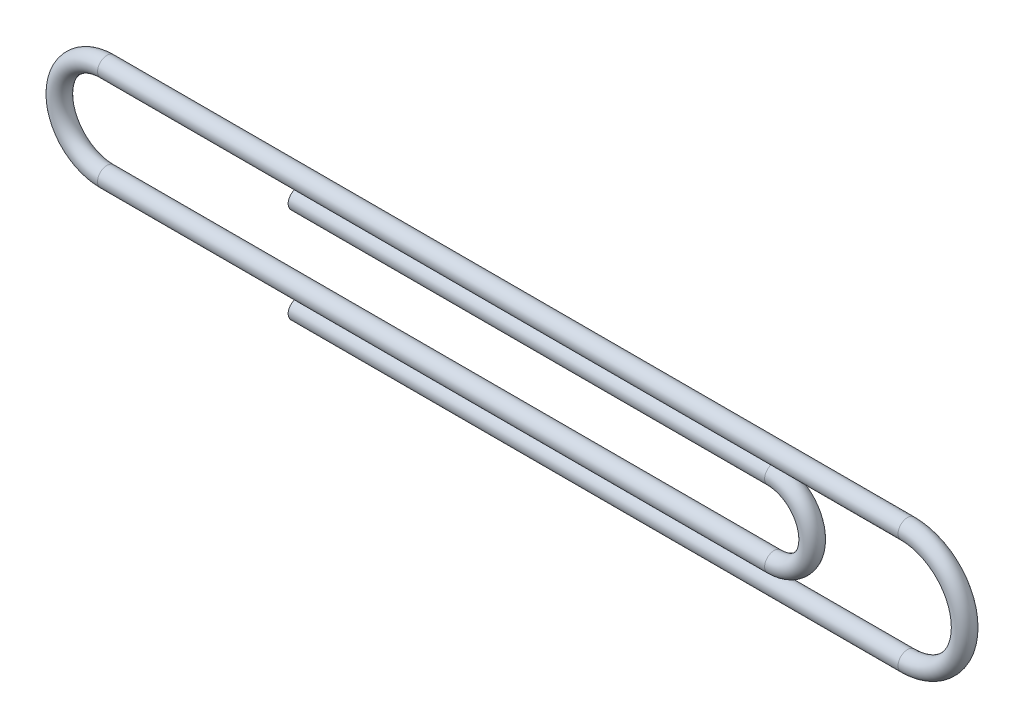
SolidWorks part; units mm, degrees
ref_plane "Front Plane" through (0, 0, 0) normal (0, 0, 1) x (1, 0, 0)
ref_plane "Top Plane" through (0, 0, 0) normal (0, 1, 0) x (1, 0, 0)
ref_plane "Right Plane" through (0, 0, 0) normal (1, 0, 0) x (0, 0, -1)
sketch "Sketch1" plane through (0, 0, 0) normal (0, 0, 1) x (1, 0, 0)
  line L0 (0, 0) -> (25, 0)
  line L1 (25, -4) -> (-10, -4)
  line L2 (-10, 1) -> (32, 1)
  line L3 (32, -5) -> (0, -5)
  arc A0 (25, 0) -> (25, -4) centre (25, -2) cw
  arc A1 (-10, -4) -> (-10, 1) centre (-10, -1.5) cw
  arc A2 (32, 1) -> (32, -5) centre (32, -2) cw
  dimension "D5" = 3
  dimension "D6" = 2
  dimension "D1" = 42
  dimension "D2" = 32
  dimension "D3" = 35
  dimension "D4" = 25
ref_plane "Plane2" through (0, 0, 0) normal (1, 0, 0) x (0, 0, -1)
sketch "Sketch3" plane through (0, 0, 0) normal (1, 0, 0) x (0, 0, -1)
  circle A0 centre (0, 0) radius 0.495
  dimension "D1" = 0.99
sweep "Sweep1" add profiles "Sketch3" path "Sketch1"
